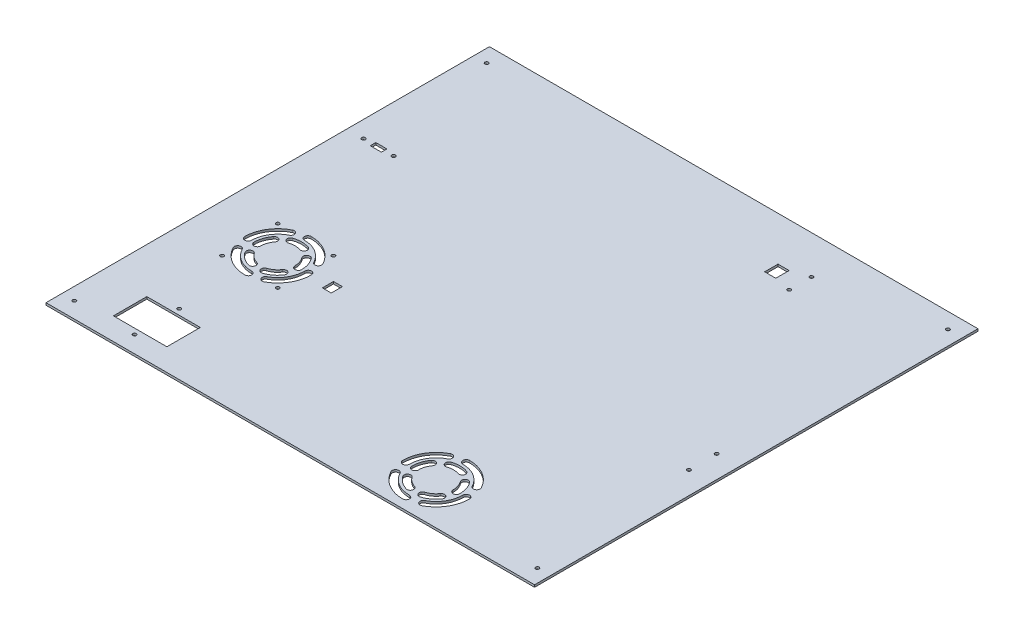
SolidWorks part; units mm, degrees
ref_plane "Alzado" through (0, 0, 0) normal (0, 0, 1) x (1, 0, 0)
ref_plane "Planta" through (0, 0, 0) normal (0, 1, 0) x (1, 0, 0)
ref_plane "Vista lateral" through (0, 0, 0) normal (1, 0, 0) x (0, 0, -1)
sketch "Croquis1" plane through (0, 0, 0) normal (0, 1, 0) x (1, 0, 0)
  line L1 (0, 0) -> (440.5, 0)
  line L2 (0, 0) -> (0, 320)
  line L3 (0, 320) -> (440.5, 320)
  line L4 (440.5, 0) -> (440.5, 320)
  dimension "D1" = 320
  dimension "D2" = 440.5
extrude "Saliente-Extruir1" add sketch "Croquis1" along normal blind 2
sketch "Croquis2" plane through (0, 2, 0) normal (0, 1, 0) x (1, 0, 0)
  line L0 (440.5, 320) -> (0, 320) construction
  line L1 (0, 320) -> (0, 0) construction
  line L2 (220.25, 320) -> (220.25, 0) construction
  line L3 (0, 0) -> (440.5, 0) construction
  line L4 (0, 160) -> (440.5, 160) construction
  line L5 (440.5, 0) -> (440.5, 320) construction
  circle A0 centre (12.5, 305) radius 1.55
  circle A1 centre (428, 305) radius 1.55
  circle A2 centre (428, 15) radius 1.55
  circle A3 centre (12.5, 15) radius 1.55
  dimension "D1" = 3.1
  dimension "D2" = 15
  dimension "D3" = 12.5
extrude "Cortar-Extruir1" cut sketch "Croquis2" against normal up to surface (2 mm away) up to face at (220.25, 0, -160)
sketch "Croquis3" plane through (0, 2, 0) normal (0, 1, 0) x (1, 0, 0)
  line L0 (439.75, 319.25) -> (0.75, 319.25)
  line L1 (0.75, 319.25) -> (0.75, 0.75)
  line L2 (0.75, 0.75) -> (439.75, 0.75)
  line L3 (439.75, 0.75) -> (439.75, 319.25)
  line L4 (0, 320) -> (0, 0)
  line L5 (0, 0) -> (440.5, 0)
  line L6 (440.5, 0) -> (440.5, 320)
  line L7 (440.5, 320) -> (0, 320)
  line L8 (0, 320) -> (0, 0)
  line L9 (0, 0) -> (440.5, 0)
  line L10 (440.5, 0) -> (440.5, 320)
  line L11 (440.5, 320) -> (0, 320)
  dimension "D1" = 0
  dimension "D2" = 0.75
extrude "Cortar-Extruir2" cut sketch "Croquis3" against normal up to surface (2 mm away) up to face at (12.5, 0, -16.55)
sketch "Croquis4" plane through (0, 2, 0) normal (0, 1, 0) x (1, 0, 0)
  line L0 (0.75, 0.75) -> (439.75, 0.75) construction
  line L1 (0.75, 319.25) -> (0.75, 0.75) construction
  line L2 (439.75, 0.75) -> (439.75, 319.25) construction
  line L4 (439.75, 319.25) -> (0.75, 319.25) construction
  line L13 (119.75, 179.25) -> (17.75, 179.25) construction
  line L14 (119.75, 179.25) -> (119.75, 103.25) construction
  line L15 (119.75, 103.25) -> (17.75, 103.25) construction
  line L16 (17.75, 179.25) -> (17.75, 103.25) construction
  line L17 (68.75, 179.25) -> (68.75, 103.25) construction
  line L18 (93.75, 116.25) -> (43.75, 116.25) construction
  line L19 (114.75, 83.75) -> (22.75, 83.75) construction
  line L20 (114.75, 83.75) -> (114.75, 198.75) construction
  line L21 (114.75, 198.75) -> (22.75, 198.75) construction
  line L22 (22.75, 83.75) -> (22.75, 198.75) construction
  line L23 (114.75, 83.75) -> (22.75, 198.75) construction
  line L24 (114.75, 198.75) -> (22.75, 83.75) construction
  line L25 (93.75, 116.25) -> (93.75, 166.25) construction
  line L26 (93.75, 166.25) -> (43.75, 166.25) construction
  line L27 (43.75, 116.25) -> (43.75, 166.25) construction
  line L28 (93.75, 116.25) -> (43.75, 166.25) construction
  line L29 (93.75, 166.25) -> (43.75, 116.25) construction
  circle A0 centre (313.9, 38.25) radius 27 construction
  arc A1 (313.9, 65.25) -> (337.8419, 50.7315) centre (313.9, 38.25) cw construction
  arc A2 (340.5021, 52.1183) -> (313.9, 68.25) centre (313.9, 38.25) ccw
  arc A3 (335.1817, 49.3447) -> (313.9, 62.25) centre (313.9, 38.25) ccw
  arc A4 (335.1817, 49.3447) -> (340.5021, 52.1183) centre (337.8419, 50.7315) ccw
  arc A5 (313.9, 68.25) -> (313.9, 62.25) centre (313.9, 65.25) ccw
  arc A6 (324.9947, 16.9683) -> (337.9, 38.25) centre (313.9, 38.25) ccw
  arc A7 (324.9947, 16.9683) -> (327.7683, 11.6479) centre (326.3815, 14.3081) ccw
  arc A8 (343.9, 38.25) -> (337.9, 38.25) centre (340.9, 38.25) ccw
  arc A9 (327.7683, 11.6479) -> (343.9, 38.25) centre (313.9, 38.25) ccw
  arc A10 (340.9, 38.25) -> (326.3815, 14.3081) centre (313.9, 38.25) cw construction
  arc A11 (292.6183, 27.1553) -> (313.9, 14.25) centre (313.9, 38.25) ccw
  arc A12 (292.6183, 27.1553) -> (287.2979, 24.3817) centre (289.9581, 25.7685) ccw
  arc A13 (313.9, 8.25) -> (313.9, 14.25) centre (313.9, 11.25) ccw
  arc A14 (287.2979, 24.3817) -> (313.9, 8.25) centre (313.9, 38.25) ccw
  arc A15 (313.9, 11.25) -> (289.9581, 25.7685) centre (313.9, 38.25) cw construction
  arc A16 (302.8053, 59.5317) -> (289.9, 38.25) centre (313.9, 38.25) ccw
  arc A17 (302.8053, 59.5317) -> (300.0317, 64.8521) centre (301.4185, 62.1919) ccw
  arc A18 (283.9, 38.25) -> (289.9, 38.25) centre (286.9, 38.25) ccw
  arc A19 (300.0317, 64.8521) -> (283.9, 38.25) centre (313.9, 38.25) ccw
  arc A20 (286.9, 38.25) -> (301.4185, 62.1919) centre (313.9, 38.25) cw construction
  circle A21 centre (313.9, 38.25) radius 18.5 construction
  arc A22 (307.9, 55.75) -> (319.9, 55.75) centre (313.9, 38.25) cw construction
  arc A23 (320.873, 58.5878) -> (306.927, 58.5878) centre (313.9, 38.25) ccw
  arc A24 (318.927, 52.9122) -> (308.873, 52.9122) centre (313.9, 38.25) ccw
  arc A25 (318.927, 52.9122) -> (320.873, 58.5878) centre (319.9, 55.75) ccw
  arc A26 (306.927, 58.5878) -> (308.873, 52.9122) centre (307.9, 55.75) ccw
  arc A27 (328.6894, 49.3641) -> (332.3976, 37.9515) centre (313.9, 38.25) cw construction
  arc A28 (335.3972, 37.903) -> (331.0877, 51.1664) centre (313.9, 38.25) ccw
  arc A29 (329.398, 37.9999) -> (326.2911, 47.5618) centre (313.9, 38.25) ccw
  arc A30 (329.398, 37.9999) -> (335.3972, 37.903) centre (332.3976, 37.9515) ccw
  arc A31 (331.0877, 51.1664) -> (326.2911, 47.5618) centre (328.6894, 49.3641) ccw
  arc A32 (329.0403, 27.6189) -> (319.3321, 20.5655) centre (313.9, 38.25) cw construction
  arc A33 (320.213, 17.6977) -> (331.4955, 25.895) centre (313.9, 38.25) ccw
  arc A34 (318.4513, 23.4332) -> (326.5852, 29.3429) centre (313.9, 38.25) ccw
  arc A35 (318.4513, 23.4332) -> (320.213, 17.6977) centre (319.3321, 20.5655) ccw
  arc A36 (331.4955, 25.895) -> (326.5852, 29.3429) centre (329.0403, 27.6189) ccw
  arc A37 (308.4679, 20.5655) -> (298.7597, 27.6189) centre (313.9, 38.25) cw construction
  arc A38 (296.3045, 25.895) -> (307.587, 17.6977) centre (313.9, 38.25) ccw
  arc A39 (301.2148, 29.3429) -> (309.3487, 23.4332) centre (313.9, 38.25) ccw
  arc A40 (301.2148, 29.3429) -> (296.3045, 25.895) centre (298.7597, 27.6189) ccw
  arc A41 (307.587, 17.6977) -> (309.3487, 23.4332) centre (308.4679, 20.5655) ccw
  arc A42 (295.4024, 37.9515) -> (299.1106, 49.3641) centre (313.9, 38.25) cw construction
  arc A43 (296.7123, 51.1664) -> (292.4028, 37.903) centre (313.9, 38.25) ccw
  arc A44 (301.5089, 47.5618) -> (298.402, 37.9999) centre (313.9, 38.25) ccw
  arc A45 (301.5089, 47.5618) -> (296.7123, 51.1664) centre (299.1106, 49.3641) ccw
  arc A46 (292.4028, 37.903) -> (298.402, 37.9999) centre (295.4024, 37.9515) ccw
  circle A47 centre (93.75, 166.25) radius 1.55
  circle A48 centre (93.75, 116.25) radius 1.55
  circle A57 centre (43.75, 116.25) radius 1.55
  circle A68 centre (43.75, 166.25) radius 1.55
  circle A69 centre (68.75, 141.25) radius 27 construction
  arc A84 (68.75, 168.25) -> (92.6919, 153.7315) centre (68.75, 141.25) cw construction
  circle A94 centre (428, 305) radius 1.55 construction
  arc A98 (95.3521, 155.1183) -> (68.75, 171.25) centre (68.75, 141.25) ccw
  arc A103 (90.0317, 152.3447) -> (68.75, 165.25) centre (68.75, 141.25) ccw
  arc A124 (90.0317, 152.3447) -> (95.3521, 155.1183) centre (92.6919, 153.7315) ccw
  arc A129 (68.75, 171.25) -> (68.75, 165.25) centre (68.75, 168.25) ccw
  circle A143 centre (119.75, 179.25) radius 1.55 construction
  circle A144 centre (17.75, 179.25) radius 1.55 construction
  circle A145 centre (17.75, 103.25) radius 1.55 construction
  circle A146 centre (119.75, 103.25) radius 1.55 construction
  circle A147 centre (114.75, 198.75) radius 1.55 construction
  circle A148 centre (22.75, 198.75) radius 1.55 construction
  circle A149 centre (22.75, 83.75) radius 1.55 construction
  circle A150 centre (114.75, 83.75) radius 1.55 construction
  arc A154 (95.7489, 141.4977) -> (81.5307, 117.4665) centre (68.75, 141.25) cw construction
  arc A159 (82.9508, 114.8239) -> (98.7487, 141.5252) centre (68.75, 141.25) ccw
  arc A164 (80.1106, 120.1091) -> (92.749, 141.4702) centre (68.75, 141.25) ccw
  circle A165 centre (68.75, 141.25) radius 18.5 construction
  arc A166 (62.75, 158.75) -> (74.75, 158.75) centre (68.75, 141.25) cw construction
  arc A167 (75.723, 161.5878) -> (61.777, 161.5878) centre (68.75, 141.25) ccw
  arc A168 (73.777, 155.9122) -> (63.723, 155.9122) centre (68.75, 141.25) ccw
  arc A169 (73.777, 155.9122) -> (75.723, 161.5878) centre (74.75, 158.75) ccw
  arc A170 (61.777, 161.5878) -> (63.723, 155.9122) centre (62.75, 158.75) ccw
  arc A171 (80.1106, 120.1091) -> (82.9508, 114.8239) centre (81.5307, 117.4665) ccw
  arc A172 (98.7487, 141.5252) -> (92.749, 141.4702) centre (95.7489, 141.4977) ccw
  arc A173 (68.9992, 114.5882) -> (45.0631, 129.009) centre (68.75, 141.25) cw construction
  arc A174 (42.3979, 127.6317) -> (69.0272, 111.5884) centre (68.75, 141.25) ccw
  arc A175 (47.7282, 130.3863) -> (68.9711, 117.5881) centre (68.75, 141.25) ccw
  arc A176 (47.7282, 130.3863) -> (42.3979, 127.6317) centre (45.0631, 129.009) ccw
  arc A177 (69.0272, 111.5884) -> (68.9711, 117.5881) centre (68.9992, 114.5882) ccw
  arc A178 (41.9999, 141.4748) -> (56.6797, 165.1231) centre (68.75, 141.25) cw construction
  arc A179 (55.326, 167.8004) -> (39, 141.5) centre (68.75, 141.25) ccw
  arc A180 (58.0333, 162.4459) -> (44.9998, 141.4496) centre (68.75, 141.25) ccw
  arc A181 (58.0333, 162.4459) -> (55.326, 167.8004) centre (56.6797, 165.1231) ccw
  arc A182 (39, 141.5) -> (44.9998, 141.4496) centre (41.9999, 141.4748) ccw
  circle A183 centre (68.75, 141.25) radius 18.5 construction
  arc A184 (83.5101, 152.4031) -> (87.2499, 141.2021) centre (68.75, 141.25) cw construction
  arc A185 (90.2499, 141.1943) -> (85.9036, 154.2117) centre (68.75, 141.25) ccw
  arc A186 (84.2499, 141.2099) -> (81.1165, 150.5945) centre (68.75, 141.25) ccw
  arc A187 (84.2499, 141.2099) -> (90.2499, 141.1943) centre (87.2499, 141.2021) ccw
  arc A188 (85.9036, 154.2117) -> (81.1165, 150.5945) centre (83.5101, 152.4031) ccw
  circle A189 centre (68.75, 141.25) radius 18.5 construction
  arc A190 (84.0871, 130.9048) -> (74.4826, 123.6606) centre (68.75, 141.25) cw construction
  arc A191 (75.4122, 120.8083) -> (86.5742, 129.2272) centre (68.75, 141.25) ccw
  arc A192 (73.553, 126.5129) -> (81.6, 132.5824) centre (68.75, 141.25) ccw
  arc A193 (73.553, 126.5129) -> (75.4122, 120.8083) centre (74.4826, 123.6606) ccw
  arc A194 (86.5742, 129.2272) -> (81.6, 132.5824) centre (84.0871, 130.9048) ccw
  circle A195 centre (68.75, 141.25) radius 18.5 construction
  arc A196 (63.5783, 123.8505) -> (53.8646, 130.8618) centre (68.75, 141.25) cw construction
  arc A197 (51.4045, 129.145) -> (62.7235, 120.9749) centre (68.75, 141.25) ccw
  arc A198 (56.3248, 132.5787) -> (64.433, 126.7262) centre (68.75, 141.25) ccw
  arc A199 (56.3248, 132.5787) -> (51.4045, 129.145) centre (53.8646, 130.8618) ccw
  arc A200 (62.7235, 120.9749) -> (64.433, 126.7262) centre (63.5783, 123.8505) ccw
  circle A201 centre (68.75, 141.25) radius 18.5 construction
  arc A202 (50.5028, 141.1667) -> (54.3731, 152.4871) centre (68.75, 141.25) cw construction
  arc A203 (52.0094, 154.3346) -> (47.5028, 141.153) centre (68.75, 141.25) ccw
  arc A204 (56.7368, 150.6397) -> (53.5027, 141.1804) centre (68.75, 141.25) ccw
  arc A205 (56.7368, 150.6397) -> (52.0094, 154.3346) centre (54.3731, 152.4871) ccw
  arc A206 (47.5028, 141.153) -> (53.5027, 141.1804) centre (50.5028, 141.1667) ccw
  point P9 (327.9, 61.3368)
  point P19 (336.9868, 24.25)
  point P26 (299.9, 15.1632)
  point P33 (290.8132, 52.25)
  point P38 (313.9, 38.25)
  point P40 (313.9, 56.75)
  point P48 (331.4945, 43.9668)
  point P51 (68.75, 141.25)
  point P57 (324.774, 23.2832)
  point P64 (303.026, 23.2832)
  point P71 (296.3055, 43.9668)
  point P76 (313.9, 38.25)
  point P88 (82.75, 164.3368)
  point P100 (91.9874, 127.5015)
  point P107 (54.9906, 118.4116)
  point P114 (46.0219, 155.3586)
  point P119 (68.75, 159.75)
  point P125 (302, 221.5)
  point P129 (86.2977, 147.109)
  point P137 (79.8902, 126.4802)
  point P147 (58.1264, 126.5317)
  point P157 (51.4838, 147.1531)
  point P171 (68.75, 141.25)
  point P183 (302, 221.5)
  dimension "D1" = 54
  dimension "D7" = 37
  dimension "D13" = 54
  dimension "D18" = 6
  dimension "D28" = 3.1
  dimension "D16" = 37
  dimension "D2" = 37.5
  dimension "D3" = 313.15
  dimension "D4" = 28
  dimension "D5" = 6
  dimension "D8" = 12
  dimension "D9" = 6
  dimension "D11" = 50
  dimension "D12" = 50
  dimension "D14" = 28
  dimension "D15" = 6
  dimension "D17" = 12
  dimension "D26" = 102
  dimension "D27" = 76
  dimension "D29" = 320
  dimension "D30" = 140
  dimension "D31" = 92
  dimension "D32" = 115
  dimension "D6" = 4
  dimension "D10" = 5
extrude "Cortar-Extruir3" cut sketch "Croquis4" against normal up to surface (2 mm away) up to face at (12.5, 0, -306.55)
sketch "Croquis5" plane through (0, 0, 0) normal (0, -1, 0) x (1, 0, 0)
  line L0 (89.75, -35.75) -> (41.75, -35.75) construction
  line L1 (89.75, -50.75) -> (41.75, -50.75)
  line L2 (89.75, -50.75) -> (89.75, -20.75)
  line L3 (89.75, -20.75) -> (41.75, -20.75)
  line L4 (41.75, -50.75) -> (41.75, -20.75)
  line L5 (439.75, -0.75) -> (439.75, -319.25) construction
  line L6 (0.75, -0.75) -> (439.75, -0.75) construction
  circle A1 centre (65.75, -15.75) radius 1.55
  circle A2 centre (65.75, -55.75) radius 1.55
  dimension "D3" = 3.1
  dimension "D1" = 48
  dimension "D2" = 30
  dimension "D4" = 5
  dimension "D5" = 24
  dimension "D6" = 350
  dimension "D7" = 20
extrude "Cortar-Extruir4" cut sketch "Croquis5" against normal up to surface (2 mm away) up to face at (297.2437, 2, -43.662)
sketch "Croquis8" plane through (0, 0, 0) normal (0, -1, 0) x (1, 0, 0)
  line L1 (439.75, -319.25) -> (0.75, -319.25)
  line L2 (439.75, -319.25) -> (439.75, -349.25)
  line L3 (439.75, -349.25) -> (0.75, -349.25)
  line L4 (0.75, -319.25) -> (0.75, -349.25)
  dimension "D1" = 30
extrude "Saliente-Extruir2" add sketch "Croquis8" against normal up to surface (2 mm away) up to face at (65.75, 2, -57.3)
sketch "Croquis10" plane through (0, 0, 0) normal (0, -1, 0) x (1, 0, 0)
  circle A0 centre (428, -305) radius 1.75
  circle A1 centre (12.5, -305) radius 1.75
  dimension "D1" = 3.5
  dimension "D2" = 3.5
extrude "Saliente-Extruir3" add sketch "Croquis10" against normal up to surface (2 mm away) up to face at (65.75, 2, -57.3)
sketch "Croquis11" plane through (0, 0, -349.25) normal (0, 0, -1) x (-1, 0, 0)
  line L4 (-0.75, 2) -> (-439.75, 2)
  line L5 (-439.75, 2) -> (-439.75, 0)
  line L6 (-439.75, 0) -> (-0.75, 0)
  line L7 (-0.75, 0) -> (-0.75, 2)
  line L8 (-0.75, 2) -> (-439.75, 2)
  line L9 (-439.75, 2) -> (-439.75, 0)
  line L10 (-439.75, 0) -> (-0.75, 0)
  line L11 (-0.75, 0) -> (-0.75, 2)
  dimension "D1" = 0
extrude "Saliente-Extruir4" add sketch "Croquis11" along normal blind 50
sketch "Croquis12" plane through (0, 0, 0) normal (0, -1, 0) x (1, 0, 0)
  line L0 (439.75, -0.75) -> (439.75, -399.25) construction
  line L1 (0.75, -399.25) -> (0.75, -0.75) construction
  line L3 (439.75, -399.25) -> (0.75, -399.25) construction
  circle A0 centre (426.75, -384.75) radius 1.55
  circle A1 centre (12.75, -384.75) radius 1.55
  dimension "D1" = 3.1
  dimension "D2" = 3.1
  dimension "D3" = 13
  dimension "D4" = 12
  dimension "D5" = 14.5
  dimension "D6" = 14.5
extrude "Cortar-Extruir8" cut sketch "Croquis12" against normal up to surface (2 mm away) up to face at (65.75, 2, -57.3)
sketch "Croquis13" plane through (0, 0, 0) normal (0, -1, 0) x (1, 0, 0)
  line L0 (439.75, -0.75) -> (439.75, -399.25) construction
  line L1 (439.75, -399.25) -> (0.75, -399.25) construction
  line L3 (309.75, -359.25) -> (299.75, -359.25)
  line L4 (309.75, -359.25) -> (309.75, -347.25)
  line L5 (309.75, -347.25) -> (299.75, -347.25)
  line L6 (299.75, -359.25) -> (299.75, -347.25)
  circle A0 centre (324.75, -364.25) radius 1.55
  circle A1 centre (324.75, -344.25) radius 1.55
  dimension "D1" = 3.1
  dimension "D2" = 20
  dimension "D3" = 115
  dimension "D4" = 35
  dimension "D5" = 10
  dimension "D6" = 12
  dimension "D7" = 40
  dimension "D8" = 140
extrude "Cortar-Extruir9" cut sketch "Croquis13" against normal up to surface (2 mm away) up to face at (426.75, 2, -386.3)
sketch "Croquis14" plane through (0, 0, 0) normal (0, -1, 0) x (1, 0, 0)
  line L1 (121.75, -146.25) -> (113.75, -146.25)
  line L2 (121.75, -146.25) -> (121.75, -136.25)
  line L3 (121.75, -136.25) -> (113.75, -136.25)
  line L4 (113.75, -146.25) -> (113.75, -136.25)
  circle A0 centre (93.75, -166.25) radius 1.55 construction
  dimension "D1" = 8
  dimension "D2" = 10
  dimension "D3" = 20
  dimension "D4" = 20
extrude "Cortar-Extruir10" cut sketch "Croquis14" against normal up to surface (2 mm away) up to face at (324.75, 2, -365.8)
sketch "Croquis15" plane through (0, 0, 0) normal (0, -1, 0) x (1, 0, 0)
  line L0 (439.75, -0.75) -> (439.75, -399.25) construction
  line L1 (439.75, -399.25) -> (0.75, -399.25) construction
  circle A0 centre (419.75, -184.25) radius 1.6
  circle A1 centre (419.75, -159.25) radius 1.6
  dimension "D1" = 3.2
  dimension "D2" = 25
  dimension "D3" = 20
  dimension "D4" = 215
extrude "Cortar-Extruir11" cut sketch "Croquis15" against normal up to surface (2 mm away) up to face at (117.75, 2, -141.25)
sketch "Croquis18" plane through (0, 0, 0) normal (0, -1, 0) x (1, 0, 0)
  line L0 (0.75, -399.25) -> (0.75, -0.75) construction
  line L1 (439.75, -399.25) -> (0.75, -399.25)
  line L2 (439.75, -399.25) -> (439.75, -398.75)
  line L3 (439.75, -398.75) -> (0.75, -398.75)
  line L4 (0.75, -399.25) -> (0.75, -398.75)
  line L6 (0.75, -0.75) -> (1.25, -0.75)
  line L7 (0.75, -0.75) -> (0.75, -398.75)
  line L8 (0.75, -398.75) -> (1.25, -398.75)
  line L9 (1.25, -0.75) -> (1.25, -398.75)
  dimension "D1" = 0.5
  dimension "D2" = 0.5
extrude "Cortar-Extruir13" cut sketch "Croquis18" against normal up to surface (2 mm away) contours L9 L6 L7 L3
sketch "Croquis19" plane through (0, 0, 0) normal (0, -1, 0) x (1, 0, 0)
  line L0 (29.75, -273.25) -> (29.75, -268.25) construction
  line L1 (34.75, -273.25) -> (24.75, -273.25)
  line L2 (34.75, -273.25) -> (34.75, -268.25)
  line L3 (34.75, -268.25) -> (24.75, -268.25)
  line L4 (24.75, -273.25) -> (24.75, -268.25)
  line L5 (29.75, -270.75) -> (16.25, -270.75) construction
  line L6 (29.75, -270.75) -> (43.25, -270.75) construction
  line L7 (41.75, -50.75) -> (89.75, -50.75) construction
  line L8 (1.25, -0.75) -> (1.25, -398.75) construction
  circle A0 centre (16.25, -270.75) radius 1.65
  circle A1 centre (43.25, -270.75) radius 1.65
  point P11 (0, 0)
  dimension "D3" = 3.3
  dimension "D4" = 3.3
  dimension "D1" = 10
  dimension "D2" = 5
  dimension "D5" = 27
  dimension "D6" = 13.5
  dimension "D7" = 220
  dimension "D8" = 15
extrude "Cortar-Extruir14" cut sketch "Croquis19" against normal up to surface (2 mm away) up to face at (12.5, 2, -16.55)
